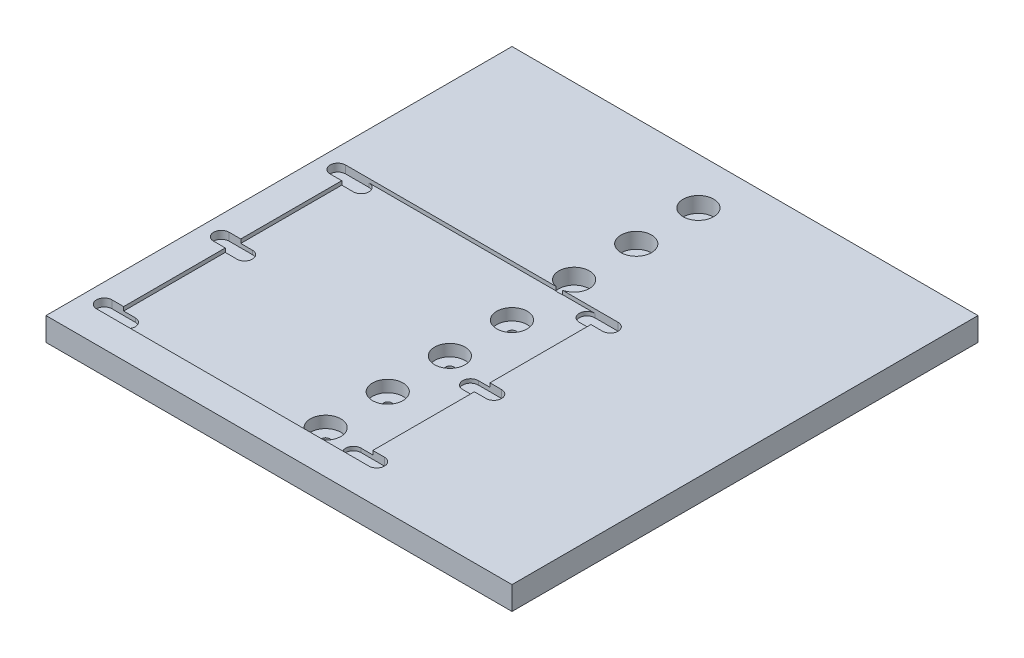
SolidWorks part; units mm, degrees
ref_plane "Front" through (0, 0, 0) normal (0, 0, 1) x (1, 0, 0)
ref_plane "Top" through (0, 0, 0) normal (0, 1, 0) x (1, 0, 0)
ref_plane "Right" through (0, 0, 0) normal (1, 0, 0) x (0, 0, -1)
sketch "Sketch2" plane through (0, 0, 0) normal (0, 1, 0) x (1, 0, 0)
  line L0 (0, 190.5) -> (0, -190.5) construction
  line L1 (-190.5, 190.5) -> (190.5, 190.5)
  line L2 (-190.5, 190.5) -> (-190.5, -190.5)
  line L3 (-190.5, -190.5) -> (190.5, -190.5)
  line L4 (190.5, 190.5) -> (190.5, -190.5)
  line L5 (-190.5, 190.5) -> (190.5, -190.5) construction
  line L6 (-190.5, -190.5) -> (190.5, 190.5) construction
  line L7 (0, 0) -> (0, 50.8) construction
  circle A0 centre (0, 0) radius 3.3782
  circle A1 centre (0, 50.8) radius 3.3782
  circle A2 centre (0, 101.6) radius 3.3782
  circle A3 centre (0, 152.4) radius 3.3782
  circle A4 centre (0, -50.8) radius 3.3782
  circle A5 centre (0, -101.6) radius 3.3782
  circle A6 centre (0, -152.4) radius 3.3782
  point P0 (0, 0)
  point P9 (0, 0)
  dimension "D2" = 6.7564
  dimension "D1" = 381
  dimension "D3" = 4
  dimension "D4" = 50.8
  dimension "D5" = 4
extrude "Bolt Holes" add sketch "Sketch2" along normal blind 19.05
sketch "Sketch3" plane through (0, 19.05, 0) normal (0, 1, 0) x (1, 0, 0)
  circle A0 centre (0, -50.8) radius 12.5
  circle A1 centre (0, 0) radius 12.5
  circle A2 centre (0, -101.6) radius 12.5
  circle A3 centre (0, 50.8) radius 12.5
  circle A4 centre (0, 101.6) radius 12.5
  circle A5 centre (0, 152.4) radius 12.5
  circle A6 centre (0, -152.4) radius 12.5
  dimension "D1" = 25
extrude "Counterbore" cut sketch "Sketch3" against normal blind 12.7
sketch "Sketch4" plane through (0, 19.05, 0) normal (0, 1, 0) x (1, 0, 0)
  line L0 (-190.5, -190.5) -> (190.5, -190.5) construction
  line L1 (-165.1, 38.608) -> (38.608, 38.608)
  line L2 (-165.1, 38.608) -> (-165.1, -165.1)
  line L3 (-165.1, -165.1) -> (38.608, -165.1)
  line L4 (38.608, 38.608) -> (38.608, -165.1)
  line L5 (-190.5, 190.5) -> (-190.5, -190.5) construction
  point P8 (-165.1, 32.9911)
  point P14 (-179.4951, 26.0773)
  dimension "D1" = 25.4
  dimension "D2" = 25.4
  dimension "D3" = 203.708
  dimension "D4" = 203.708
extrude "al_pocket" cut sketch "Sketch4" against normal blind 3.175
sketch "Sketch5" plane through (0, 19.05, 0) normal (0, 1, 0) x (1, 0, 0)
  line L0 (38.608, -165.1) -> (38.608, 38.608) construction
  line L5 (38.608, -165.1) -> (38.608, 38.608) construction
  line L6 (38.608, 38.608) -> (2.7577, 38.608) construction
  line L7 (-174.625, 32.258) -> (-155.575, 32.258) construction
  line L8 (-165.1, -165.1) -> (38.608, -165.1) construction
  line L10 (-165.1, 38.608) -> (-165.1, -165.1) construction
  line L11 (-174.625, 38.608) -> (-155.575, 38.608)
  line L12 (-174.625, 25.908) -> (-155.575, 25.908)
  line L13 (-174.625, -158.75) -> (-155.575, -158.75) construction
  line L14 (-174.625, -152.4) -> (-155.575, -152.4)
  line L15 (-174.625, -165.1) -> (-155.575, -165.1)
  line L16 (-165.1, 38.608) -> (-165.1, -165.1) construction
  line L17 (-165.1, -165.1) -> (38.608, -165.1) construction
  line L18 (-174.625, -62.992) -> (-155.575, -62.992) construction
  line L19 (-174.625, -56.642) -> (-155.575, -56.642)
  line L20 (-174.625, -69.342) -> (-155.575, -69.342)
  line L21 (29.083, 32.258) -> (48.133, 32.258) construction
  line L22 (29.083, 38.608) -> (48.133, 38.608)
  line L23 (29.083, 25.908) -> (48.133, 25.908)
  line L24 (29.083, -158.75) -> (48.133, -158.75) construction
  line L25 (29.083, -152.4) -> (48.133, -152.4)
  line L26 (29.083, -165.1) -> (48.133, -165.1)
  line L27 (29.083, -62.992) -> (48.133, -62.992) construction
  line L28 (29.083, -56.642) -> (48.133, -56.642)
  line L29 (29.083, -69.342) -> (48.133, -69.342)
  arc A4 (-174.625, 38.608) -> (-174.625, 25.908) centre (-174.625, 32.258) ccw
  arc A5 (-155.575, 25.908) -> (-155.575, 38.608) centre (-155.575, 32.258) ccw
  arc A6 (-174.625, -152.4) -> (-174.625, -165.1) centre (-174.625, -158.75) ccw
  arc A7 (-155.575, -165.1) -> (-155.575, -152.4) centre (-155.575, -158.75) ccw
  arc A8 (-174.625, -56.642) -> (-174.625, -69.342) centre (-174.625, -62.992) ccw
  arc A9 (-155.575, -69.342) -> (-155.575, -56.642) centre (-155.575, -62.992) ccw
  arc A10 (29.083, 38.608) -> (29.083, 25.908) centre (29.083, 32.258) ccw
  arc A11 (48.133, 25.908) -> (48.133, 38.608) centre (48.133, 32.258) ccw
  arc A12 (29.083, -152.4) -> (29.083, -165.1) centre (29.083, -158.75) ccw
  arc A13 (48.133, -165.1) -> (48.133, -152.4) centre (48.133, -158.75) ccw
  arc A14 (29.083, -56.642) -> (29.083, -69.342) centre (29.083, -62.992) ccw
  arc A15 (48.133, -69.342) -> (48.133, -56.642) centre (48.133, -62.992) ccw
  point P3 (-165.1, 38.608)
  point P5 (38.1, 16.5253)
  point P6 (-165.1, 32.258)
  point P14 (-165.1, -158.75)
  point P19 (-165.1, -156.5045)
  point P27 (-159.2797, -29.821)
  point P28 (-165.1, -62.992)
  point P33 (-165.1, -72.0977)
  point P34 (-159.2797, -29.821)
  point P37 (31.1653, 32.4407)
  point P38 (38.608, 32.258)
  point P46 (38.608, -158.75)
  point P52 (36.9856, -35.4803)
  point P53 (38.608, -62.992)
  point P59 (38.1, -69.85)
  point P64 (38.1, -148.7296)
  dimension "D2" = 19.05
  dimension "0.25" = 6.35
  dimension "D4" = 6.35
  dimension "D7" = 6.35
  dimension "D10" = 6.35
  dimension "D13" = 6.35
  dimension "D15" = 6.35
  dimension "D1" = 19.05
  dimension "D3" = 6.35
  dimension "D5" = 6.35
  dimension "D6" = 19.05
  dimension "D8" = 101.6
  dimension "D9" = 19.05
  dimension "D11" = 6.35
  dimension "D12" = 19.05
  dimension "D14" = 19.05
  dimension "D16" = 101.6
  dimension "D17" = 6.35
extrude "Relief" cut sketch "Sketch5" against normal blind 6.35
